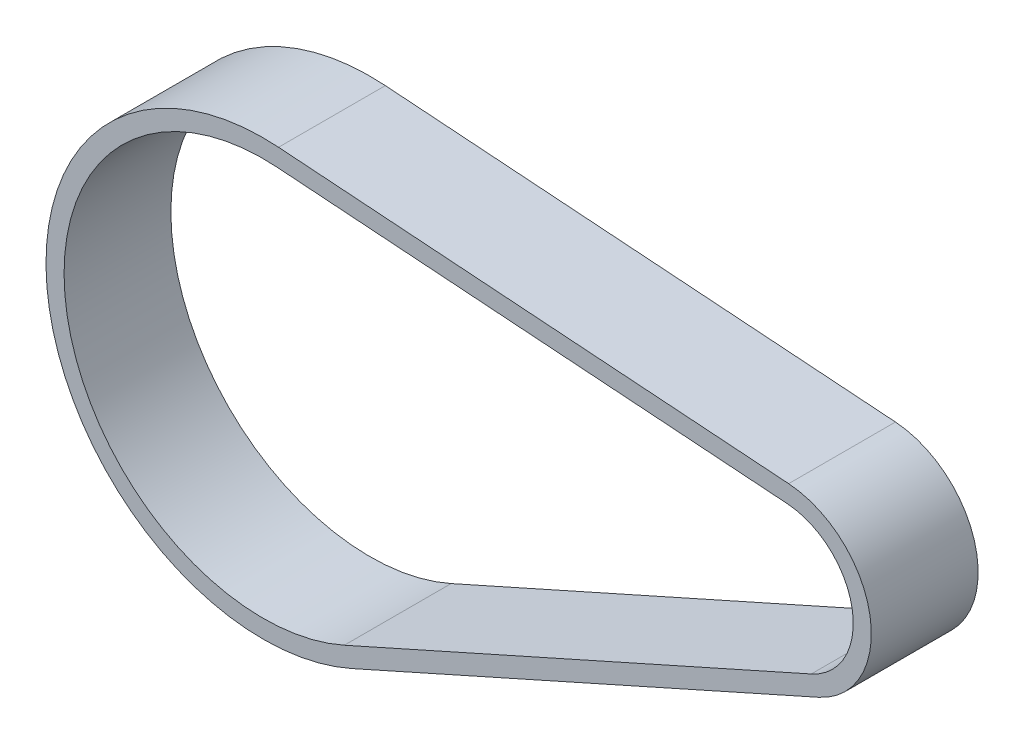
SolidWorks part; units mm, degrees
material "NEOPRENE"
ref_plane "Front Plane" through (0, 0, 0) normal (0, 0, 1) x (1, 0, 0)
ref_plane "Top Plane" through (0, 0, 0) normal (0, 1, 0) x (1, 0, 0)
ref_plane "Right Plane" through (0, 0, 0) normal (1, 0, 0) x (0, 0, -1)
sketch "Sketch2" plane through (0, 0, 0) normal (0, 0, 1) x (1, 0, 0)
  line L0 (0, 0) -> (1, 0) construction
  line L1 (0, 0) -> (0, 1) construction
  line L2 (2.1639, 30.4231) -> (73.8118, 25.3271)
  line L3 (78.0228, 1.4454) -> (12.4387, -27.8483)
  arc A0 (12.4387, -27.8483) -> (2.1639, 30.4231) centre (0, 0) cw
  arc A1 (73.8118, 25.3271) -> (78.0228, 1.4454) centre (72.925, 12.8586) cw
extrude "Extrude-Thin1" add sketch "Sketch2" against normal blind 15 thin
